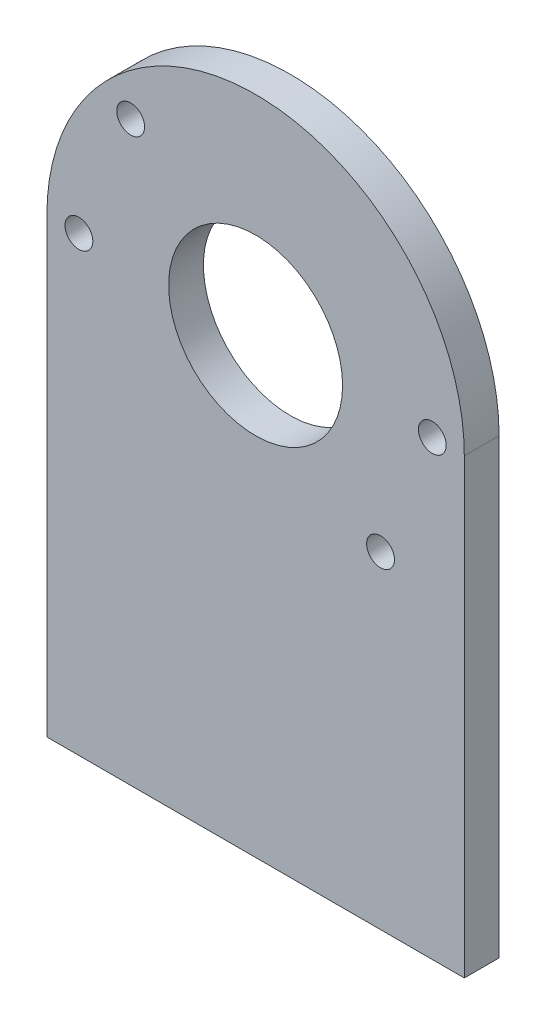
SolidWorks part; units mm, degrees
ref_plane "前视基准面" through (0, 0, 0) normal (0, 0, 1) x (1, 0, 0)
ref_plane "上视基准面" through (0, 0, 0) normal (0, 1, 0) x (1, 0, 0)
ref_plane "右视基准面" through (0, 0, 0) normal (1, 0, 0) x (0, 0, -1)
sketch "草图1" plane through (0, 0, 0) normal (0, 0, 1) x (1, 0, 0)
  line L0 (0, 0) -> (-17.96, 0) construction
  line L1 (-17.96, 0) -> (-17.96, 17.96) construction
  line L2 (0, 0) -> (-25.4, 0) construction
  line L3 (0, 0) -> (0, 10) construction
  line L4 (0, 0) -> (17.96, 0) construction
  line L5 (17.96, 0) -> (17.96, -17.96) construction
  line L6 (0, 0) -> (0, -65) construction
  line L7 (30, -65) -> (-30, -65)
  line L8 (-30, -65) -> (-30, 0)
  line L9 (30, -65) -> (30, 0)
  circle A0 centre (-17.96, 17.96) radius 2
  circle A1 centre (-25.4, 0) radius 2
  circle A2 centre (25.4, 0) radius 2
  circle A3 centre (17.96, -17.96) radius 2
  arc A4 (30, 0) -> (-30, 0) centre (0, 0) ccw
  circle A5 centre (0, 0) radius 12.5
extrude "凸台-拉伸1" add sketch "草图1" along normal blind 5
